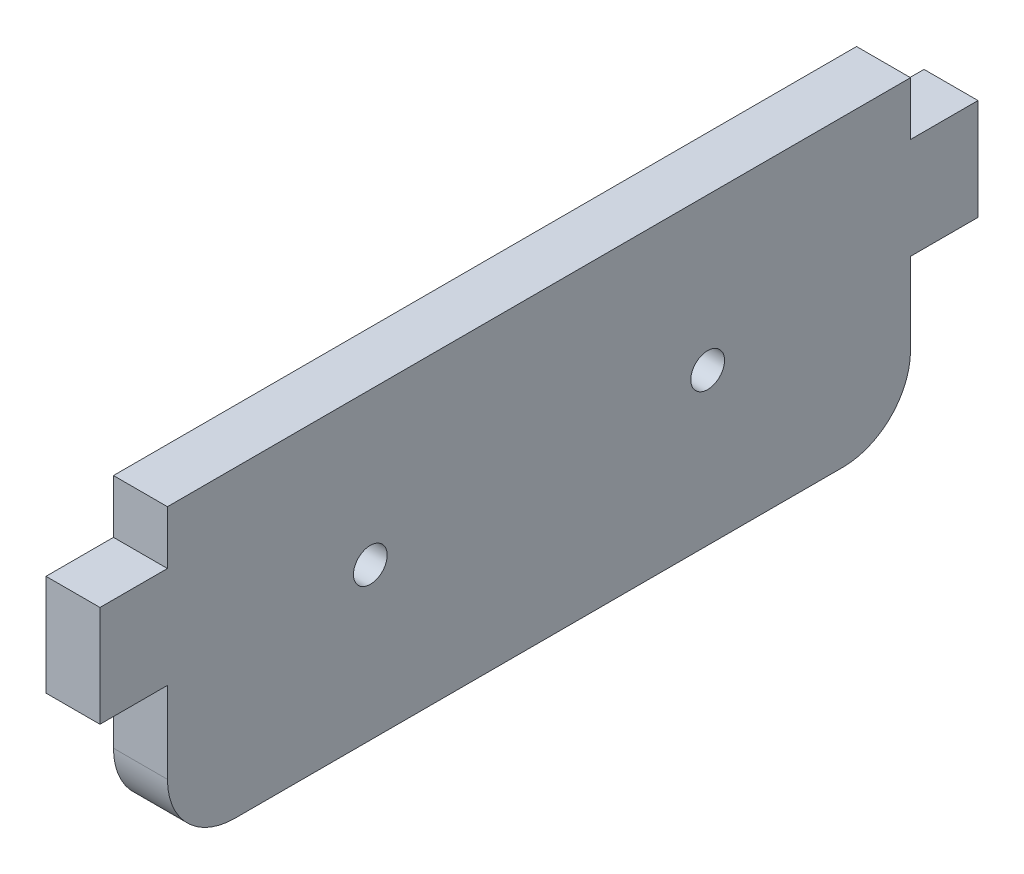
SolidWorks part; units mm, degrees
ref_plane "Front Plane" through (0, 0, 0) normal (0, 0, 1) x (1, 0, 0)
ref_plane "Top Plane" through (0, 0, 0) normal (0, 1, 0) x (1, 0, 0)
ref_plane "Right Plane" through (0, 0, 0) normal (1, 0, 0) x (0, 0, -1)
sketch "Sketch1" plane through (0, 0, 0) normal (0, 0, 1) x (1, 0, 0)
  line L0 (-51, -85.5) -> (-51, -70.5) construction
  line L1 (-59, -70.5) -> (-51, -70.5)
  line L2 (-59, -70.5) -> (-59, -85.5)
  line L3 (-59, -85.5) -> (-51, -85.5)
  line L4 (-51, -70.5) -> (-51, -85.5)
  line L5 (-59, -70.5) -> (-51, -85.5) construction
  line L6 (-59, -85.5) -> (-51, -70.5) construction
  point P0 (-55, -78)
extrude "Boss-Extrude1" add sketch "Sketch1" against normal blind 10
sketch "Sketch2" plane through (0, 0, -10) normal (0, 0, -1) x (-1, 0, 0)
  line L1 (51, -62.5656) -> (59, -62.5656)
  line L2 (51, -62.5656) -> (51, -92.5656)
  line L4 (59, -62.5656) -> (59, -92.5656)
  line L5 (51, -62.5656) -> (59, -92.5656) construction
  line L6 (51, -92.5656) -> (59, -62.5656) construction
  line L8 (51, -92.5656) -> (51, -107.5656)
  line L9 (51, -107.5656) -> (59, -107.5656)
  line L10 (59, -92.5656) -> (59, -107.5656)
  point P0 (55, -77.5656)
  dimension "D1" = 30
  dimension "D2" = 15
extrude "Boss-Extrude2" add sketch "Sketch2" along normal up to surface (110.14 mm away)
fillet "Fillet1" radius 10 2 edges at (-55, -107.5656, -10) (-55, -107.5656, -120.14)
ref_plane "Plane1" through (0, 0, -65.07) normal (0, 0, 1) x (1, 0, 0)
mirror "Mirror1" about plane through (0, 0, -65.07) normal (0, 0, 1) of "Boss-Extrude1"
sketch "Sketch4" plane through (-51, 0, 0) normal (1, 0, 0) x (0, 0, -1)
  line L0 (65.07, -62.5656) -> (65.07, -107.5656) construction
  line L1 (120.14, -62.5656) -> (10, -62.5656) construction
  line L2 (110.14, -107.5656) -> (20, -107.5656) construction
  circle A0 centre (40.07, -85.0656) radius 2.5
  circle A1 centre (90.07, -85.0656) radius 2.5
  dimension "D1" = 5
  dimension "D2" = 50
extrude "Cut-Extrude1" cut sketch "Sketch4" against normal blind 10
